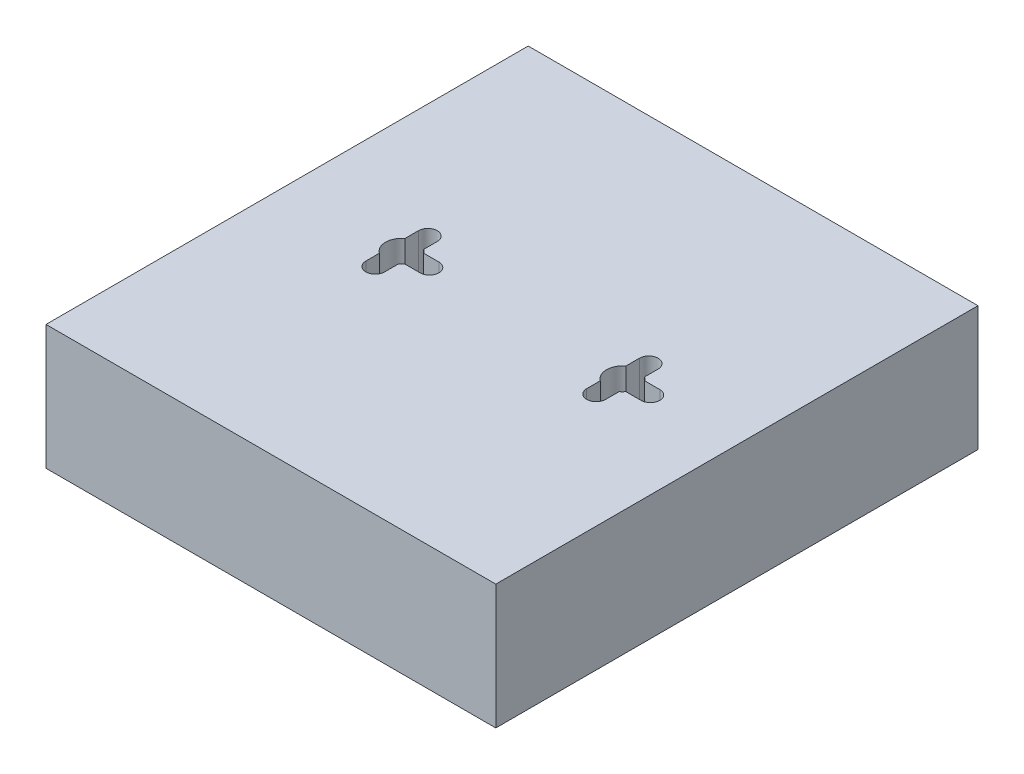
SolidWorks part; units mm, degrees
ref_plane "Front Plane" through (0, 0, 0) normal (0, 0, 1) x (1, 0, 0)
ref_plane "Top Plane" through (0, 0, 0) normal (0, 1, 0) x (1, 0, 0)
ref_plane "Right Plane" through (0, 0, 0) normal (1, 0, 0) x (0, 0, -1)
sketch "Sketch1" plane through (0, 0, 0) normal (0, 1, 0) x (1, 0, 0)
  line L0 (70.2401, 56.0118) -> (70.2401, 44.9882) construction
  line L1 (0, 0) -> (94.2086, 0)
  line L2 (0, 0) -> (0, 101)
  line L3 (0, 101) -> (94.2086, 101)
  line L4 (94.2086, 0) -> (94.2086, 101)
  line L5 (72.2086, 56.0118) -> (72.2086, 44.9882)
  line L6 (68.2716, 56.0118) -> (68.2716, 44.9882)
  line L7 (70.2401, 50.5) -> (76.0948, 50.5) construction
  line L8 (70.2401, 52.4685) -> (76.0948, 52.4685)
  line L9 (70.2401, 48.5315) -> (76.0948, 48.5315)
  line L10 (70.2401, 50.5) -> (66.9127, 50.5) construction
  line L11 (0, 50.5) -> (94.2086, 50.5) construction
  line L12 (47.1043, 0) -> (47.1043, 101) construction
  line L13 (23.9685, 56.0118) -> (23.9685, 44.9882) construction
  line L14 (25.937, 56.0118) -> (25.937, 44.9882)
  line L15 (22, 56.0118) -> (22, 44.9882)
  line L16 (23.9685, 50.5) -> (29.8232, 50.5) construction
  line L17 (23.9685, 52.4685) -> (29.8232, 52.4685)
  line L18 (23.9685, 48.5315) -> (29.8232, 48.5315)
  line L19 (23.9685, 50.5) -> (20.6411, 50.5) construction
  circle A0 centre (70.2401, 50.5) radius 3.3274
  arc A1 (72.2086, 56.0118) -> (68.2716, 56.0118) centre (70.2401, 56.0118) ccw
  arc A2 (68.2716, 44.9882) -> (72.2086, 44.9882) centre (70.2401, 44.9882) ccw
  arc A3 (70.2401, 52.4685) -> (70.2401, 48.5315) centre (70.2401, 50.5) ccw
  arc A4 (76.0948, 48.5315) -> (76.0948, 52.4685) centre (76.0948, 50.5) ccw
  circle A5 centre (23.9685, 50.5) radius 3.3274
  arc A6 (25.937, 56.0118) -> (22, 56.0118) centre (23.9685, 56.0118) ccw
  arc A7 (22, 44.9882) -> (25.937, 44.9882) centre (23.9685, 44.9882) ccw
  arc A8 (23.9685, 52.4685) -> (23.9685, 48.5315) centre (23.9685, 50.5) ccw
  arc A9 (29.8232, 48.5315) -> (29.8232, 52.4685) centre (29.8232, 50.5) ccw
  point P9 (70.2401, 50.5)
  point P14 (73.1675, 50.5)
  point P20 (70.2401, 43.0197)
  point P21 (70.2401, 57.9803)
  point P27 (78.0633, 50.5)
  point P29 (73.4222, 51.177)
  point P30 (0, 0)
  point P35 (23.9685, 50.5)
  point P40 (26.8959, 50.5)
  point P46 (23.9685, 43.0197)
  point P47 (23.9685, 57.9803)
  point P50 (31.7917, 50.5)
  point P51 (0, 0)
  dimension "D6" = 6.6548
  dimension "D11" = 6.6548
  dimension "D1" = 94.2086
  dimension "D2" = 101
  dimension "D3" = 14.9606
  dimension "D4" = 11.1506
  dimension "D5" = 3.937
  dimension "D7" = 22
  dimension "D8" = 14.9606
  dimension "D9" = 3.937
  dimension "D10" = 11.1506
  dimension "D12" = 22
extrude "Boss-Extrude1" add sketch "Sketch1" along normal blind 26.1 contours L1 L4 L3 L2 A9 L18 A5 L14 A7 L15 A6 L17 A4 L9 A0 L5 A2 L6 A1 L8
sketch "Sketch2" plane through (0, 0, 0) normal (0, -1, 0) x (1, 0, 0)
  line L0 (0, 0) -> (94.2086, 0) construction
  line L1 (11.938, -20.32) -> (82.2706, -20.32) construction
  line L2 (11.938, -20.32) -> (11.938, -85.76) construction
  line L3 (11.938, -85.76) -> (82.2706, -85.76) construction
  line L4 (82.2706, -20.32) -> (82.2706, -85.76) construction
  line L5 (0, -101) -> (94.2086, -101) construction
  line L6 (94.2086, 0) -> (94.2086, -101) construction
  line L7 (0, 0) -> (0, -101) construction
  circle A0 centre (11.938, -20.32) radius 5.461
  circle A1 centre (82.2706, -20.32) radius 5.461
  circle A2 centre (11.938, -85.76) radius 5.461
  circle A3 centre (82.2706, -85.76) radius 5.461
  dimension "D5" = 10.922
  dimension "D1" = 20.32
  dimension "D2" = 15.24
  dimension "D3" = 11.938
  dimension "D4" = 11.938
extrude "Boss-Extrude2" add sketch "Sketch2" along normal blind 2.54
sketch "Sketch3" plane through (0, 0, -101) normal (0, 0, -1) x (-1, 0, 0)
  line L0 (-94.2086, 0) -> (0, 26.1) construction
  line L2 (-87.4011, 21.2605) -> (-6.8075, 21.2605)
  line L3 (-87.4011, 21.2605) -> (-87.4011, 4.8395)
  line L4 (-87.4011, 4.8395) -> (-6.8075, 4.8395)
  line L5 (-6.8075, 21.2605) -> (-6.8075, 4.8395)
  line L6 (-87.4011, 21.2605) -> (-6.8075, 4.8395) construction
  line L7 (-87.4011, 4.8395) -> (-6.8075, 21.2605) construction
  point P4 (-47.1043, 13.05)
extrude "Cut-Extrude1" cut sketch "Sketch3" against normal blind 5
ref_plane "Plane1" through (47.1043, 0, 0) normal (-1, 0, 0) x (0, 0, 1)
equation "\"D4@Sketch2\"=\"D3@Sketch2\""
